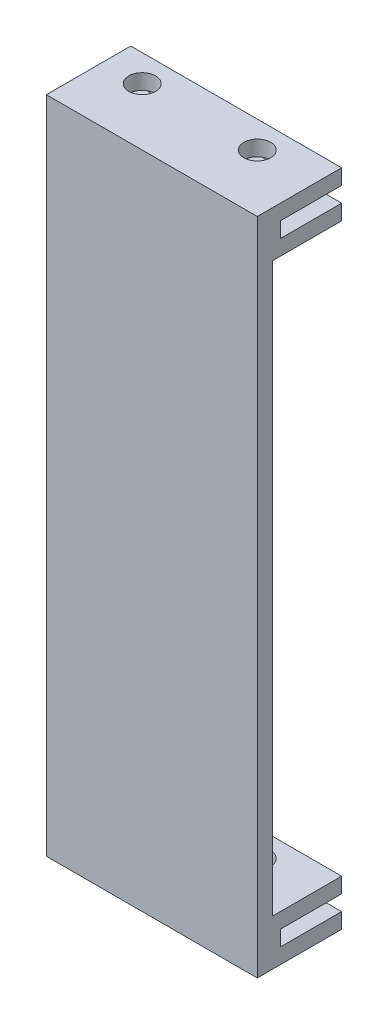
SolidWorks part; units mm, degrees
material "PET"
ref_plane "前视基准面" through (0, 0, 0) normal (0, 0, 1) x (1, 0, 0)
ref_plane "上视基准面" through (0, 0, 0) normal (0, 1, 0) x (1, 0, 0)
ref_plane "右视基准面" through (0, 0, 0) normal (1, 0, 0) x (0, 0, -1)
other "Configuration Table"
sketch "草图1" plane through (0, 0, 0) normal (0, 1, 0) x (1, 0, 0)
  line L1 (-15, 5.5) -> (15, 5.5)
  line L2 (-15, 5.5) -> (-15, -5.5)
  line L3 (-15, -5.5) -> (15, -5.5)
  line L4 (15, 5.5) -> (15, -5.5)
  line L5 (-15, 5.5) -> (15, -5.5) construction
  line L6 (-15, -5.5) -> (15, 5.5) construction
  point P0 (0, 0)
  dimension "D1" = 30
  dimension "D2" = 11
extrude "凸台-拉伸1" add sketch "草图1" along normal blind 6
sketch "草图2" plane through (-15, 0, 0) normal (-1, 0, 0) x (0, 0, 1)
  line L0 (-5.5, 6) -> (-5.5, 0) construction
  line L1 (-13.5, 2) -> (2.5, 2)
  line L2 (-13.5, 2) -> (-13.5, 4)
  line L3 (-13.5, 4) -> (2.5, 4)
  line L4 (2.5, 2) -> (2.5, 4)
  line L5 (-13.5, 2) -> (2.5, 4) construction
  line L6 (-13.5, 4) -> (2.5, 2) construction
  line L7 (-5.5, 6) -> (5.5, 6) construction
  line L8 (5.5, 6) -> (5.5, 0) construction
  point P0 (-5.5, 3)
  dimension "D1" = 2
  dimension "D2" = 3
extrude "切除-拉伸1" cut sketch "草图2" against normal blind 144
sketch "草图3" plane through (0, 6, 0) normal (0, 1, 0) x (1, 0, 0)
  line L0 (2, 5.5) -> (-2, 5.5)
  line L1 (15, 5.5) -> (-15, 5.5) construction
  line L2 (-2, 5.5) -> (-2, -3.5)
  line L3 (-2, -3.5) -> (-15, -3.5)
  line L4 (-15, 5.5) -> (-15, -5.5) construction
  line L5 (-15, -3.5) -> (-15, -5.5)
  line L6 (-15, -5.5) -> (15, -5.5)
  line L7 (-15, -5.5) -> (15, -5.5) construction
  line L8 (0, 5.5) -> (0, -5.5) construction
  line L9 (15, -3.5) -> (15, -5.5)
  line L10 (2, -3.5) -> (15, -3.5)
  line L11 (2, 5.5) -> (2, -3.5)
  dimension "D1" = 2
  dimension "D2" = 2
extrude "凸台-拉伸2" add sketch "草图3" along normal blind 74
sketch "草图4" plane through (0, 6, 0) normal (0, 1, 0) x (1, 0, 0)
  line L0 (-15, 5.5) -> (-15, 2) construction
  line L1 (-15, 5.5) -> (-15, -3.5) construction
  line L2 (-15, 2) -> (15, 2) construction
  line L3 (15, -3.5) -> (15, 5.5) construction
  line L4 (0, 5.5) -> (0, -5.5) construction
  line L5 (2, 5.5) -> (-2, 5.5) construction
  line L6 (-15, -5.5) -> (15, -5.5) construction
  circle A0 centre (-7.5, 2) radius 1.75
  circle A1 centre (7.5, 2) radius 1.75
  point P10 (0, 2)
  dimension "D2" = 7.5
  dimension "D3" = 3.5
  dimension "D1" = 3.5
extrude "切除-拉伸2" cut sketch "草图4" against normal blind 144
sketch "草图5" plane through (-15, 0, 0) normal (-1, 0, 0) x (0, 0, 1)
  line L1 (-5.5, 0) -> (5.5, 0)
  line L2 (-5.5, 0) -> (-5.5, 80)
  line L3 (-5.5, 80) -> (5.5, 80)
  line L4 (5.5, 0) -> (5.5, 80)
extrude "切除-拉伸3" cut sketch "草图5" against normal blind 2.5
sketch "草图6" plane through (0, 6, 0) normal (0, 1, 0) x (1, 0, 0)
  line L0 (-12.5, -2.5) -> (-12.5, 7.5) construction
  line L1 (-22.5, 7.5) -> (-25.5, 7.5)
  line L2 (-12.5, -2.5) -> (-12.5, -5.5)
  arc A0 (-22.5, 7.5) -> (-12.5, -2.5) centre (-12.5, 7.5) ccw
  arc A1 (-25.5, 7.5) -> (-12.5, -5.5) centre (-12.5, 7.5) ccw
  dimension "D1" = 10
ref_plane "基准面1" through (0, 43, 0) normal (0, 1, 0) x (1, 0, 0)
mirror "镜向1" about plane through (0, 43, 0) normal (0, 1, 0) of "切除-拉伸3", "凸台-拉伸1", "切除-拉伸1", "切除-拉伸2"
